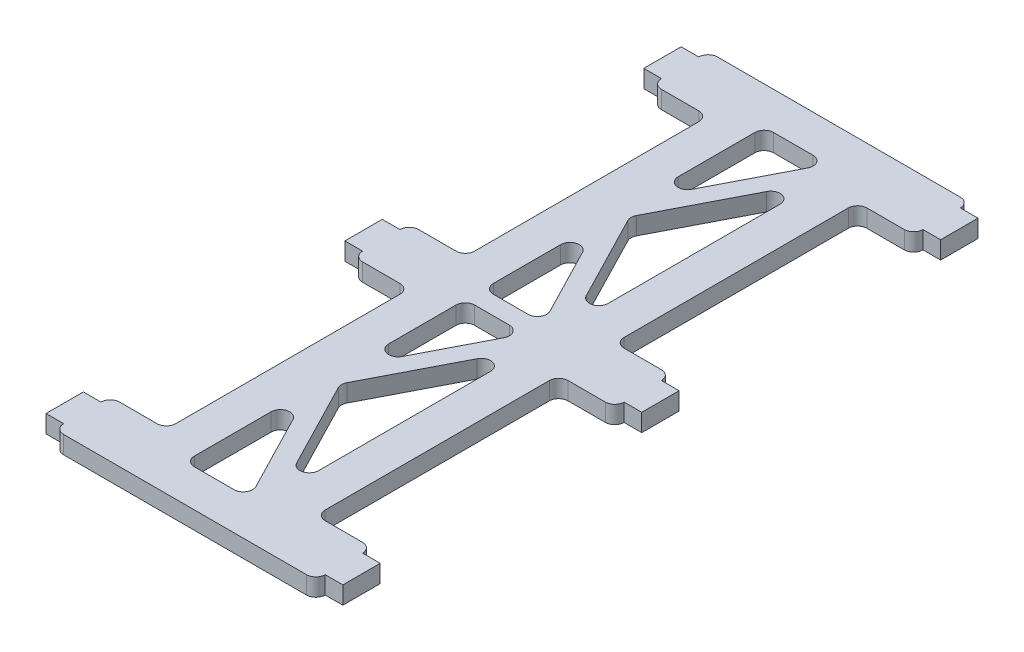
SolidWorks part; units mm, degrees
ref_plane "Front Plane" through (0, 0, 0) normal (0, 0, 1) x (1, 0, 0)
ref_plane "Top Plane" through (0, 0, 0) normal (0, 1, 0) x (1, 0, 0)
ref_plane "Right Plane" through (0, 0, 0) normal (1, 0, 0) x (0, 0, -1)
sketch "Sketch1" plane through (0, 34.29, 0) normal (0, 1, 0) x (1, 0, 0)
  line L0 (16.0528, 190.5) -> (19.05, 190.5) construction
  line L1 (0, -190.5) -> (0, 187.198) construction
  line L2 (38.1028, 187.198) -> (35.1028, 187.198) construction
  line L3 (35.1028, -190.5) -> (38.1, -190.5) construction
  line L5 (-12.7, 65.0875) -> (12.7, 65.0875)
  line L6 (-12.7, 65.0875) -> (-12.7, 176.2125)
  line L7 (-12.7, 176.2125) -> (12.7, 176.2125)
  line L8 (12.7, 65.0875) -> (12.7, 176.2125)
  line L9 (-12.7, 65.0875) -> (12.7, 176.2125) construction
  line L10 (-12.7, 176.2125) -> (12.7, 65.0875) construction
  point P0 (0, 120.65)
  dimension "D1" = 111.125
  dimension "D2" = 25.4
  dimension "D3" = 14.2875
extrude "Boss-Extrude1" add sketch "Sketch1" along normal mid plane 3 contours L7 L8 L5 L6
sketch "Sketch2" plane through (0, 35.79, 0) normal (0, 1, 0) x (1, 0, 0)
  line L0 (0, 176.2125) -> (0, 65.0186) construction
  line L1 (-12.7, 176.2125) -> (12.7, 176.2125) construction
  line L2 (12.7, 120.65) -> (-12.7, 120.65) construction
  line L3 (12.7, 65.0875) -> (12.7, 176.2125) construction
  line L4 (-12.7, 65.0875) -> (-12.7, 176.2125) construction
  line L5 (-22.225, 176.2125) -> (-12.7, 166.6875) construction
  line L6 (22.225, 166.6875) -> (12.7, 166.6875)
  line L7 (22.225, 166.6875) -> (22.225, 176.2125)
  line L8 (22.225, 176.2125) -> (12.7, 176.2125)
  line L9 (12.7, 166.6875) -> (12.7, 176.2125)
  line L10 (22.225, 166.6875) -> (12.7, 176.2125) construction
  line L11 (22.225, 176.2125) -> (12.7, 166.6875) construction
  line L12 (-22.225, 166.6875) -> (-12.7, 176.2125) construction
  line L13 (-12.7, 166.6875) -> (-12.7, 176.2125)
  line L14 (-22.225, 176.2125) -> (-12.7, 176.2125)
  line L15 (-22.225, 166.6875) -> (-22.225, 176.2125)
  line L16 (-22.225, 166.6875) -> (-12.7, 166.6875)
  line L17 (22.225, 115.8875) -> (12.7, 115.8875)
  line L18 (22.225, 115.8875) -> (22.225, 125.4125)
  line L19 (22.225, 125.4125) -> (12.7, 125.4125)
  line L20 (12.7, 115.8875) -> (12.7, 125.4125)
  line L21 (22.225, 115.8875) -> (12.7, 125.4125) construction
  line L22 (22.225, 125.4125) -> (12.7, 115.8875) construction
  line L23 (-12.7, 115.8875) -> (-12.7, 125.4125)
  line L24 (-22.225, 125.4125) -> (-12.7, 125.4125)
  line L25 (-22.225, 115.8875) -> (-22.225, 125.4125)
  line L26 (-22.225, 115.8875) -> (-12.7, 115.8875)
  line L27 (-22.225, 125.4125) -> (-12.7, 115.8875) construction
  line L28 (-22.225, 115.8875) -> (-12.7, 125.4125) construction
  line L29 (22.225, 65.0875) -> (12.7, 65.0875)
  line L30 (22.225, 65.0875) -> (22.225, 74.6125)
  line L31 (22.225, 74.6125) -> (12.7, 74.6125)
  line L32 (12.7, 65.0875) -> (12.7, 74.6125)
  line L33 (22.225, 65.0875) -> (12.7, 74.6125) construction
  line L34 (22.225, 74.6125) -> (12.7, 65.0875) construction
  line L35 (-12.7, 65.0875) -> (-12.7, 74.6125)
  line L36 (-22.225, 74.6125) -> (-12.7, 74.6125)
  line L37 (-22.225, 65.0875) -> (-22.225, 74.6125)
  line L38 (-22.225, 65.0875) -> (-12.7, 65.0875)
  line L39 (-22.225, 74.6125) -> (-12.7, 65.0875) construction
  line L40 (-22.225, 65.0875) -> (-12.7, 74.6125) construction
  point P11 (17.4625, 171.45)
  point P21 (-17.4625, 171.45)
  point P24 (17.4625, 120.65)
  point P33 (-17.4625, 120.65)
  point P34 (17.4625, 69.85)
  point P43 (-17.4625, 69.85)
  dimension "D1" = 9.525
  dimension "D2" = 9.525
  dimension "D3" = 3
extrude "Boss-Extrude2" add sketch "Sketch2" against normal up to surface (3 mm away) up to face at (0, 32.79, -120.65)
sketch "Sketch4" plane through (0, 35.79, 0) normal (0, 1, 0) x (1, 0, 0)
  line L0 (12.7, 125.4125) -> (12.7, 166.6875) construction
  line L1 (-6.35, 169.8625) -> (6.35, 169.8625)
  line L2 (-6.35, 169.8625) -> (-6.35, 71.4375)
  line L3 (-6.35, 71.4375) -> (6.35, 71.4375)
  line L4 (6.35, 169.8625) -> (6.35, 71.4375)
  line L5 (-6.35, 169.8625) -> (6.35, 71.4375) construction
  line L6 (-6.35, 71.4375) -> (6.35, 169.8625) construction
  line L7 (-12.7, 125.4125) -> (-12.7, 166.6875) construction
  line L8 (-22.225, 176.2125) -> (22.225, 176.2125) construction
  line L9 (-22.225, 65.0875) -> (22.225, 65.0875) construction
  line L10 (-6.35, 96.0438) -> (6.35, 96.0438) construction
  line L12 (-6.35, 96.0438) -> (6.35, 120.65) construction
  line L13 (6.35, 120.65) -> (-6.35, 145.2563) construction
  line L14 (6.35, 71.4375) -> (-6.35, 96.0438) construction
  line L15 (-6.35, 145.2563) -> (6.35, 145.2563) construction
  line L17 (7.7607, 72.1656) -> (-4.6953, 96.299)
  line L18 (-6.35, 145.2563) -> (6.35, 169.8625) construction
  line L19 (6.35, 120.65) -> (-6.35, 120.65) construction
  line L20 (-7.7607, 96.7718) -> (4.9393, 121.3781)
  line L21 (4.9393, 70.7094) -> (-8.0047, 95.7885)
  line L22 (6.35, 119.0625) -> (-6.35, 119.0625)
  line L23 (4.9393, 119.9219) -> (-8.1365, 145.2562)
  line L24 (-8.1365, 145.2562) -> (4.9393, 170.5906)
  line L25 (-4.6953, 96.299) -> (7.9145, 169.5933) construction
  line L26 (-4.9393, 95.3157) -> (7.7607, 119.9219)
  line L27 (-6.35, 96.0438) -> (6.35, 169.8625) construction
  line L29 (6.35, 122.2375) -> (-6.35, 122.2375)
  line L30 (-8.0047, 95.7885) -> (4.7855, 170.1317) construction
  line L31 (7.7607, 121.3781) -> (-4.5635, 145.2563)
  line L32 (-4.5635, 145.2563) -> (7.7607, 169.1344)
  point P0 (0, 120.65)
  dimension "D1" = 6.35
  dimension "D2" = 6.35
  dimension "D3" = 6.35
  dimension "D4" = 6.35
  dimension "D7" = 1.5875
  dimension "D8" = 1.5875
  dimension "D9" = 1.5875
  dimension "D10" = 1.5875
extrude "Cut-Extrude1" cut sketch "Sketch4" against normal through all contours L3 L21 L2 | L26 L17 L4 | L20 L22 L2 | L29 L23 L2 | L32 L31 L4 | L2 L24 L1
fillet "Fillet1" radius 1.5875 38 edges at (-6.35, 34.29, -92.5825) (6.35, 34.29, -74.8988) (22.225, 34.29, -65.0875) (22.225, 34.29, -74.6125) (12.7, 34.29, -74.6125) (12.7, 34.29, -115.8875) (22.225, 34.29, -115.8875) (22.225, 34.29, -125.4125) (12.7, 34.29, -125.4125) (12.7, 34.29, -166.6875) (22.225, 34.29, -166.6875) (22.225, 34.29, -176.2125) (-22.225, 34.29, -166.6875) (-12.7, 34.29, -166.6875) (-12.7, 34.29, -125.4125) (-22.225, 34.29, -125.4125) (-22.225, 34.29, -115.8875) (-12.7, 34.29, -115.8875) (-12.7, 34.29, -74.6125) (-22.225, 34.29, -74.6125) (-22.225, 34.29, -65.0875) (4.5635, 34.29, -71.4375) (-22.225, 34.29, -176.2125) (-6.35, 34.29, -141.795) (3.7442, 34.29, -122.2375) (-6.35, 34.29, -122.2375) (6.35, 34.29, -117.1887) (6.35, 34.29, -124.1113) (-4.5635, 34.29, -145.2563) (6.35, 34.29, -166.4012) (-6.35, 34.29, -169.8625) (4.5635, 34.29, -169.8625) (-6.35, 34.29, -148.7175) (-6.35, 34.29, -99.505) (-6.35, 34.29, -119.0625) (3.7442, 34.29, -119.0625) (-6.35, 34.29, -71.4375) (-4.5635, 34.29, -96.0438)
sketch "Sketch5" plane through (0, 35.79, 0) normal (0, 1, 0) x (1, 0, 0)
  line L0 (22.225, 168.275) -> (22.225, 174.625) construction
  line L1 (25.225, 168.275) -> (22.225, 168.275)
  line L2 (25.225, 168.275) -> (25.225, 174.625)
  line L3 (25.225, 174.625) -> (22.225, 174.625)
  line L4 (22.225, 168.275) -> (22.225, 174.625)
  line L5 (25.225, 168.275) -> (22.225, 174.625) construction
  line L6 (25.225, 174.625) -> (22.225, 168.275) construction
  line L7 (22.225, 168.275) -> (22.225, 174.625) construction
  line L8 (22.225, 171.45) -> (23.725, 171.45) construction
  line L9 (0, 196.0278) -> (0, 0) construction
  line L10 (-22.225, 171.45) -> (-23.725, 171.45) construction
  line L11 (-25.225, 174.625) -> (-22.225, 168.275) construction
  line L12 (-25.225, 168.275) -> (-22.225, 174.625) construction
  line L13 (-22.225, 168.275) -> (-22.225, 174.625)
  line L14 (-25.225, 174.625) -> (-22.225, 174.625)
  line L15 (-25.225, 168.275) -> (-25.225, 174.625)
  line L16 (-25.225, 168.275) -> (-22.225, 168.275)
  line L17 (25.225, 117.475) -> (22.225, 117.475)
  line L18 (25.225, 117.475) -> (25.225, 123.825)
  line L19 (25.225, 123.825) -> (22.225, 123.825)
  line L20 (22.225, 117.475) -> (22.225, 123.825)
  line L21 (25.225, 117.475) -> (22.225, 123.825) construction
  line L22 (25.225, 123.825) -> (22.225, 117.475) construction
  line L23 (22.225, 120.65) -> (23.725, 120.65) construction
  line L24 (-22.225, 117.475) -> (-22.225, 123.825)
  line L25 (-25.225, 123.825) -> (-22.225, 123.825)
  line L26 (-25.225, 117.475) -> (-25.225, 123.825)
  line L27 (-25.225, 117.475) -> (-22.225, 117.475)
  line L28 (-22.225, 120.65) -> (-23.725, 120.65) construction
  line L29 (-25.225, 123.825) -> (-22.225, 117.475) construction
  line L30 (-25.225, 117.475) -> (-22.225, 123.825) construction
  line L31 (25.225, 66.675) -> (22.225, 66.675)
  line L32 (25.225, 66.675) -> (25.225, 73.025)
  line L33 (25.225, 73.025) -> (22.225, 73.025)
  line L34 (22.225, 66.675) -> (22.225, 73.025)
  line L35 (25.225, 66.675) -> (22.225, 73.025) construction
  line L36 (25.225, 73.025) -> (22.225, 66.675) construction
  line L37 (22.225, 69.85) -> (23.725, 69.85) construction
  line L38 (-22.225, 66.675) -> (-22.225, 73.025)
  line L39 (-25.225, 73.025) -> (-22.225, 73.025)
  line L40 (-25.225, 66.675) -> (-25.225, 73.025)
  line L41 (-25.225, 66.675) -> (-22.225, 66.675)
  line L42 (-22.225, 69.85) -> (-23.725, 69.85) construction
  line L43 (-25.225, 73.025) -> (-22.225, 66.675) construction
  line L44 (-25.225, 66.675) -> (-22.225, 73.025) construction
  line L45 (-23.725, 171.45) -> (-23.725, 120.65) construction
  point P0 (23.725, 171.45)
  point P7 (23.725, 120.65)
  point P21 (-23.725, 171.45)
  point P35 (-23.725, 120.65)
  point P36 (23.725, 69.85)
  point P49 (-23.725, 69.85)
  dimension "D1" = 3
  dimension "D2" = 6.35
  dimension "D4" = 50.8
  dimension "D3" = 3
extrude "Boss-Extrude3" add sketch "Sketch5" against normal up to surface (3 mm away) up to face at (-2.8486, 32.79, -113.8749)
